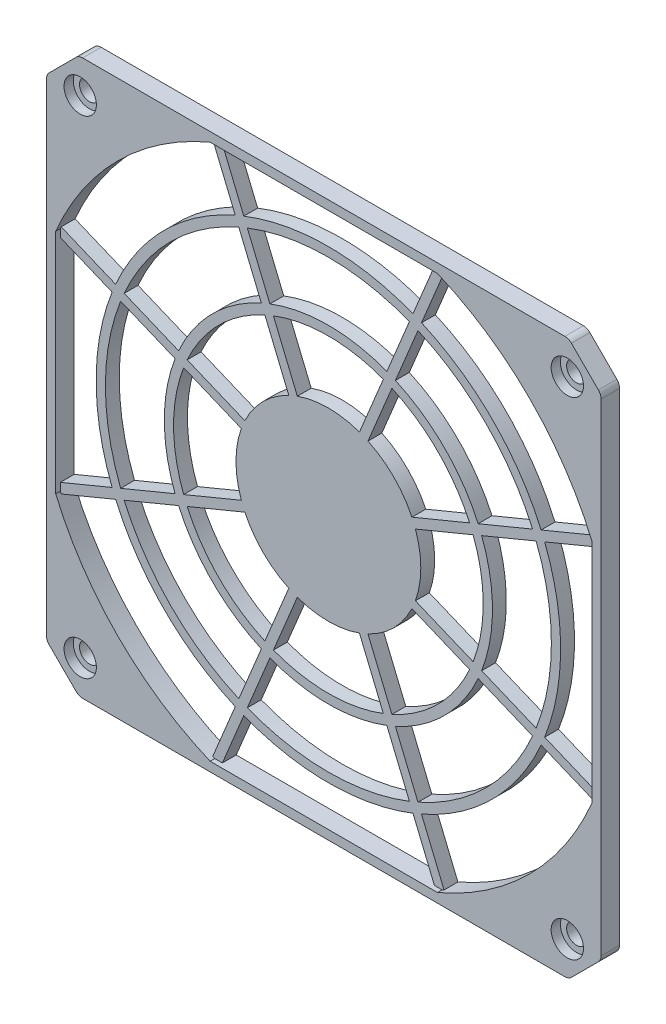
SolidWorks part; units mm, degrees
ref_plane "Front Plane" through (0, 0, 0) normal (0, 0, 1) x (1, 0, 0)
ref_plane "Top Plane" through (0, 0, 0) normal (0, 1, 0) x (1, 0, 0)
ref_plane "Right Plane" through (0, 0, 0) normal (1, 0, 0) x (0, 0, -1)
sketch "Sketch1" plane through (0, 0, 0) normal (0, 0, 1) x (1, 0, 0)
  line L0 (-24.5967, 58) -> (24.5967, 58)
  line L1 (-60, -60) -> (60, -60)
  line L2 (-60, -60) -> (-60, 60)
  line L3 (-60, 60) -> (60, 60)
  line L4 (60, -60) -> (60, 60)
  line L5 (0, 60) -> (0, -60) construction
  line L6 (-60, 0) -> (60, 0) construction
  line L7 (-60, 58) -> (60, 58) construction
  line L8 (-60, 60) -> (60, 60) construction
  line L9 (58, 24.5967) -> (58, -24.5967)
  line L10 (24.5967, -58) -> (-24.5967, -58)
  line L11 (-58, -24.5967) -> (-58, 24.5967)
  line L13 (-52.7, -52.7) -> (52.7, -52.7) construction
  line L14 (-52.7, -52.7) -> (-52.7, 52.7) construction
  line L15 (-52.7, 52.7) -> (52.7, 52.7) construction
  line L16 (52.7, -52.7) -> (52.7, 52.7) construction
  line L17 (0, 52.7) -> (0, -52.7) construction
  line L18 (-52.7, 0) -> (52.7, 0) construction
  arc A0 (-24.5967, 58) -> (-58, 24.5967) centre (0, 0) ccw
  arc A1 (-58, -24.5967) -> (-24.5967, -58) centre (0, 0) ccw
  arc A2 (24.5967, -58) -> (58, -24.5967) centre (0, 0) ccw
  arc A3 (58, 24.5967) -> (24.5967, 58) centre (0, 0) ccw
  circle A4 centre (-52.7, 52.7) radius 2.15
  circle A5 centre (52.7, 52.7) radius 2.15
  circle A6 centre (-52.7, -52.7) radius 2.15
  circle A7 centre (52.7, -52.7) radius 2.15
  point P0 (0, 0)
  point P21 (0, 0)
  dimension "D3" = 126
  dimension "D8" = 4.3
  dimension "D1" = 120
  dimension "D2" = 120
  dimension "D6" = 105.4
  dimension "D7" = 105.4
  dimension "D4" = 2
  dimension "D5" = 4
extrude "Boss-Extrude1" add sketch "Sketch1" along normal blind 4
chamfer "Chamfer1" distance 7 4 edges at (-60, -60, 2) (60, -60, 2) (60, 60, 2) (-60, 60, 2)
sketch "Sketch2" plane through (0, 0, 0) normal (0, 0, 1) x (1, 0, 0)
  circle A0 centre (0, 0) radius 20
  dimension "D1" = 40
extrude "Boss-Extrude2" add sketch "Sketch2" along normal blind 3 separate body
sketch "Sketch3" plane through (0, 0, 0) normal (0, 0, 1) x (1, 0, 0)
  line L0 (6.697, 16.1679) -> (24.2047, 58.4354)
  line L1 (0, 0) -> (0, 71.9458) construction
  line L2 (16.1679, 6.697) -> (58.4354, 24.2047)
  line L3 (16.1679, -6.697) -> (58.4354, -24.2047)
  line L4 (6.697, -16.1679) -> (24.2047, -58.4354)
  line L5 (-6.697, -16.1679) -> (-24.2047, -58.4354)
  line L6 (-16.1679, -6.697) -> (-58.4354, -24.2047)
  line L7 (-16.1679, 6.697) -> (-58.4354, 24.2047)
  line L8 (-6.697, 16.1679) -> (-24.2047, 58.4354)
  circle A0 centre (0, 0) radius 17.5 construction
  circle A1 centre (0, 0) radius 34.5
  circle A2 centre (0, 0) radius 49.25
  point P22 (0, 0)
  dimension "D2" = 35
  dimension "D5" = 69
  dimension "D6" = 98.5
  dimension "D1" = 22.5
  dimension "D4" = 63.25
  dimension "D3" = 8
extrude "Extrude-Thin1" add sketch "Sketch3" along normal blind 3 thin thin type mid plane wall 2
fillet "Fillet1" radius 2 8 edges at (53, 60, 2) (60, 53, 2) (60, -53, 2) (53, -60, 2) (-53, -60, 2) (-60, -53, 2) (-53, 60, 2) (-60, 53, 2)
sketch "Sketch4" plane through (0, 0, 4) normal (0, 0, 1) x (1, 0, 0)
  circle A0 centre (-52.7, 52.7) radius 3.5
  circle A1 centre (52.7, 52.7) radius 3.5
  circle A2 centre (52.7, -52.7) radius 3.5
  circle A3 centre (-52.7, -52.7) radius 3.5
  dimension "D1" = 7
extrude "Cut-Extrude1" cut sketch "Sketch4" against normal blind 2
